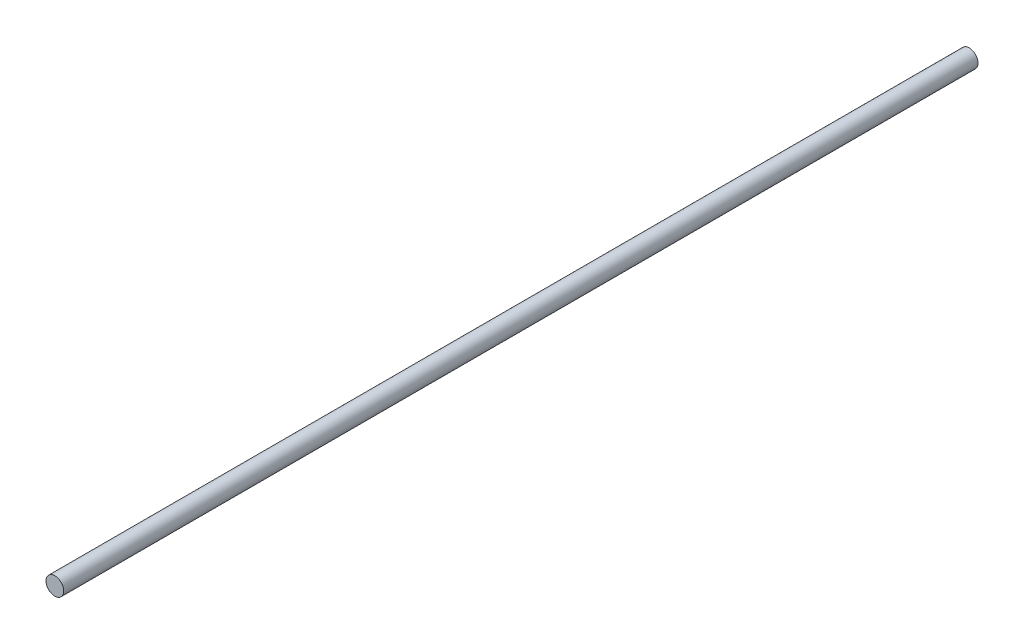
SolidWorks part; units mm, degrees
ref_plane "Front Plane" through (0, 0, 0) normal (0, 0, 1) x (1, 0, 0)
ref_plane "Top Plane" through (0, 0, 0) normal (0, 1, 0) x (1, 0, 0)
ref_plane "Right Plane" through (0, 0, 0) normal (1, 0, 0) x (0, 0, -1)
sketch "Sketch1" plane through (0, 0, 0) normal (0, 0, 1) x (1, 0, 0)
  circle A0 centre (0, 0) radius 2
  dimension "D1" = 4
extrude "Boss-Extrude1" add sketch "Sketch1" along normal blind 207
